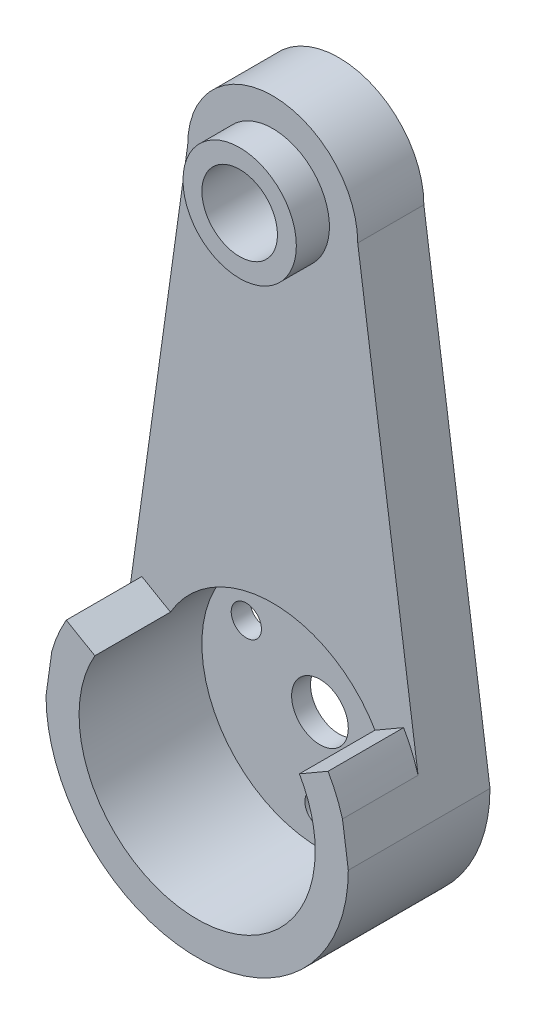
SolidWorks part; units mm, degrees
ref_plane "Plan de face" through (0, 0, 0) normal (0, 0, 1) x (1, 0, 0)
ref_plane "Plan de dessus" through (0, 0, 0) normal (0, 1, 0) x (1, 0, 0)
ref_plane "Plan de droite" through (0, 0, 0) normal (1, 0, 0) x (0, 0, -1)
sketch "Esquisse1" plane through (0, 0, 0) normal (0, 0, 1) x (1, 0, 0)
  line L0 (-16.3093, 0) -> (24.5372, 0) construction
  line L1 (9, 0) -> (16, -50)
  line L2 (-9, 0) -> (-16, -50)
  line L3 (-16, -50) -> (16, -50) construction
  line L4 (0, 0) -> (0, -50) construction
  arc A0 (-9, 0) -> (9, 0) centre (0, 0) cw
  arc A1 (-16, -50) -> (16, -50) centre (0, -50) ccw
  dimension "D1" = 9
  dimension "D2" = 16
  dimension "D3" = 50
extrude "Boss.-Extru.1" add sketch "Esquisse1" along normal blind 7
sketch "Esquisse2" plane through (0, 0, 7) normal (0, 0, 1) x (1, 0, 0)
  line L0 (0, 0) -> (0, -66) construction
  line L1 (16, -50) -> (-16, -50) construction
  circle A0 centre (0, -50) radius 3
  arc A1 (-16, -50) -> (16, -50) centre (0, -50) ccw construction
  dimension "D1" = 6
extrude "Enlèv. mat.-Extru.1" cut sketch "Esquisse2" against normal blind 7
sketch "Esquisse3" plane through (0, 0, 7) normal (0, 0, 1) x (1, 0, 0)
  line L0 (0, -50) -> (0, 0) construction
  line L1 (0, -50) -> (7.7942, -45.5) construction
  line L2 (0, -50) -> (-7.7942, -45.5) construction
  line L3 (0, -50) -> (0, -59) construction
  circle A3 centre (0, -59) radius 1.6
  circle A4 centre (-7.7942, -45.5) radius 1.6
  circle A5 centre (7.7942, -45.5) radius 1.6
  dimension "D5" = 9
  dimension "D6" = 9
extrude "Enlèv. mat.-Extru.2" cut sketch "Esquisse3" against normal blind 7
ref_plane "Plan1" through (0, 10, 0) normal (0, 1, 0) x (1, 0, 0)
sketch "Esquisse5" plane through (0, 0, 7) normal (0, 0, 1) x (1, 0, 0)
  circle A0 centre (0, -50) radius 12.5
  dimension "D1" = 25
extrude "Enlèv. mat.-Extru.5" cut sketch "Esquisse5" against normal blind 5
sketch "Esquisse17" plane through (0, 0, 7) normal (0, 0, 1) x (1, 0, 0)
  circle A0 centre (0, 0) radius 4
  circle A1 centre (0, 0) radius 6
extrude "Boss.-Extru.6" add sketch "Esquisse17" along normal blind 3.5
sketch "Esquisse18" plane through (0, 0, 7) normal (0, 0, 1) x (1, 0, 0)
  line L0 (0, -50) -> (-13.8564, -42) construction
  line L1 (0, -50) -> (13.8564, -42) construction
  line L2 (-13.8564, -42) -> (-10.8253, -43.75)
  line L3 (10.8253, -43.75) -> (13.8564, -42)
  circle A0 centre (0, -50) radius 12.5
  circle A1 centre (0, -50) radius 16
  circle M2 centre (0, -50) radius 12.5
  line M4 (-9, 0) -> (-16, -50)
  arc M5 (-16, -50) -> (16, -50) centre (0, -50) ccw
  line M6 (16, -50) -> (9, 0)
  dimension "D1" = 120
extrude "Boss.-Extru.8" add sketch "Esquisse18" along normal blind 8 contours A1 L3 L2 M6 M2 M4 M5
sketch "Esquisse19" plane through (0, 0, 7) normal (0, 0, 1) x (1, 0, 0)
  circle A0 centre (0, 0) radius 4
extrude "Enlèv. mat.-Extru.6" cut sketch "Esquisse19" against normal blind 8
